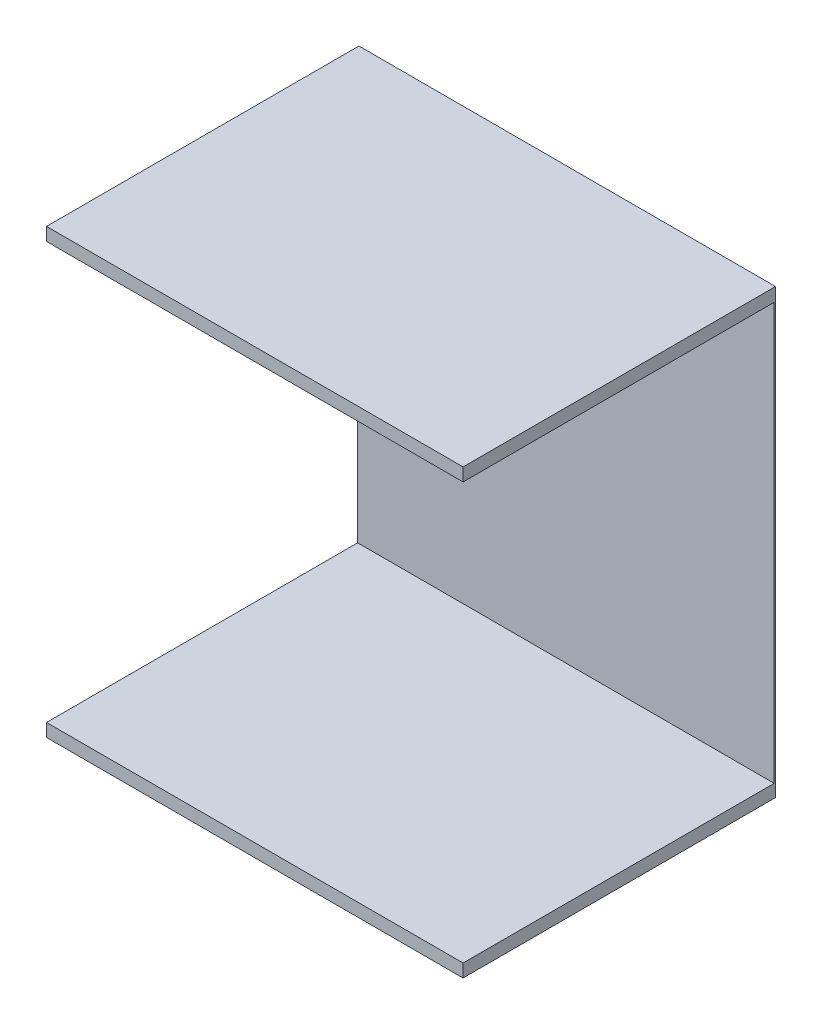
SolidWorks part; units mm, degrees
ref_plane "Front Plane" through (0, 0, 0) normal (0, 0, 1) x (1, 0, 0)
ref_plane "Top Plane" through (0, 0, 0) normal (0, 1, 0) x (1, 0, 0)
ref_plane "Right Plane" through (0, 0, 0) normal (1, 0, 0) x (0, 0, -1)
sketch "Sketch1" plane through (0, 0, 0) normal (0, 0, 1) x (1, 0, 0)
  line L2 (0, 0) -> (0, 6.35)
  line L3 (0, 6.35) -> (203.2, 6.35)
  line L5 (0, -209.55) -> (203.2, -209.55)
  line L6 (0, -209.55) -> (0, -203.2)
  line L7 (0, -203.2) -> (203.2, -203.2)
  line L8 (203.2, -209.55) -> (203.2, -203.2)
  line L10 (400.0965, -209.55) -> (406.4, -208.7829)
  line L12 (0, -203.2) -> (0, 0)
  line L13 (203.2, -209.55) -> (400.0965, -209.55)
  line L14 (0, 0) -> (203.2, 0)
  line L15 (203.2, 0) -> (203.2, 6.35)
  dimension "D1" = 203.2
  dimension "D2" = 6.35
  dimension "D3" = 6.35
  dimension "D4" = 203.2
  dimension "D5" = 0
  dimension "D6" = 6.35
  dimension "D7" = 6.35
extrude "Boss-Extrude1" add sketch "Sketch1" along normal blind 152.4
sketch "Sketch3" plane through (0, 0, 0) normal (0, 0, -1) x (-1, 0, 0)
  line L9 (-203.2, -209.55) -> (-203.2, 6.35)
  line L10 (-203.2, 6.35) -> (0, 6.35)
  line L11 (0, 6.35) -> (0, -209.55)
  line L12 (0, -209.55) -> (-203.2, -209.55)
  dimension "D1" = 203.2
extrude "Boss-Extrude2" add sketch "Sketch3" against normal blind 0.635
